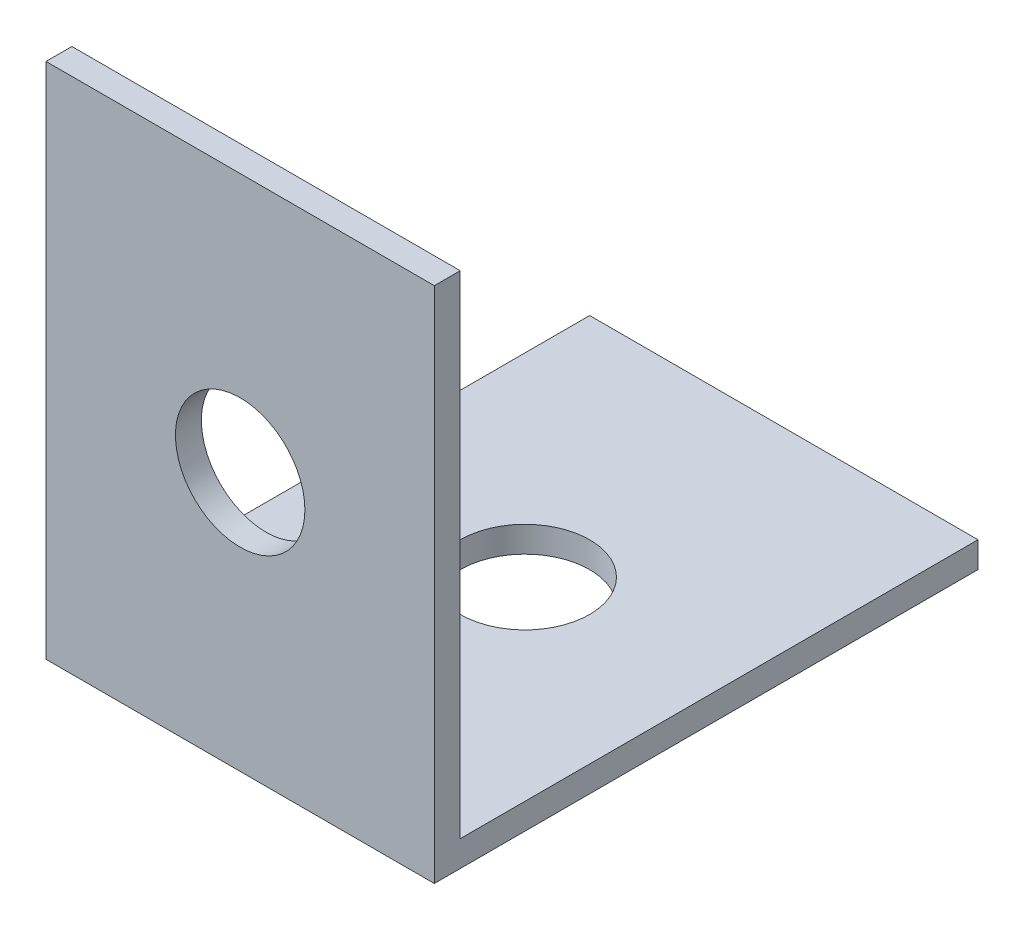
SolidWorks part; units mm, degrees
ref_plane "Front Plane" through (0, 0, 0) normal (0, 0, 1) x (1, 0, 0)
ref_plane "Top Plane" through (0, 0, 0) normal (0, 1, 0) x (1, 0, 0)
ref_plane "Right Plane" through (0, 0, 0) normal (1, 0, 0) x (0, 0, -1)
sketch "Sketch1" plane through (0, 0, 0) normal (0, 1, 0) x (1, 0, 0)
  line L1 (-7.5, -10) -> (7.5, -10)
  line L2 (-7.5, -10) -> (-7.5, 10)
  line L3 (-7.5, 10) -> (7.5, 10)
  line L4 (7.5, -10) -> (7.5, 10)
  line L5 (-7.5, -10) -> (7.5, 10) construction
  line L6 (-7.5, 10) -> (7.5, -10) construction
  circle A0 centre (0, 0) radius 2.5
  point P0 (0, 0)
  dimension "D3" = 5
  dimension "D1" = 20
  dimension "D2" = 15
extrude "Boss-Extrude1" add sketch "Sketch1" along normal blind 1
sketch "Sketch2" plane through (0, 0, 10) normal (0, 0, 1) x (1, 0, 0)
  line L1 (-7.5, 0) -> (7.5, 0)
  line L2 (-7.5, 0) -> (-7.5, 20)
  line L3 (-7.5, 20) -> (7.5, 20)
  line L4 (7.5, 0) -> (7.5, 20)
  circle A0 centre (0, 10) radius 2.5
  dimension "D2" = 5
  dimension "D1" = 20
  dimension "D3" = 10
extrude "Boss-Extrude2" add sketch "Sketch2" along normal blind 1
